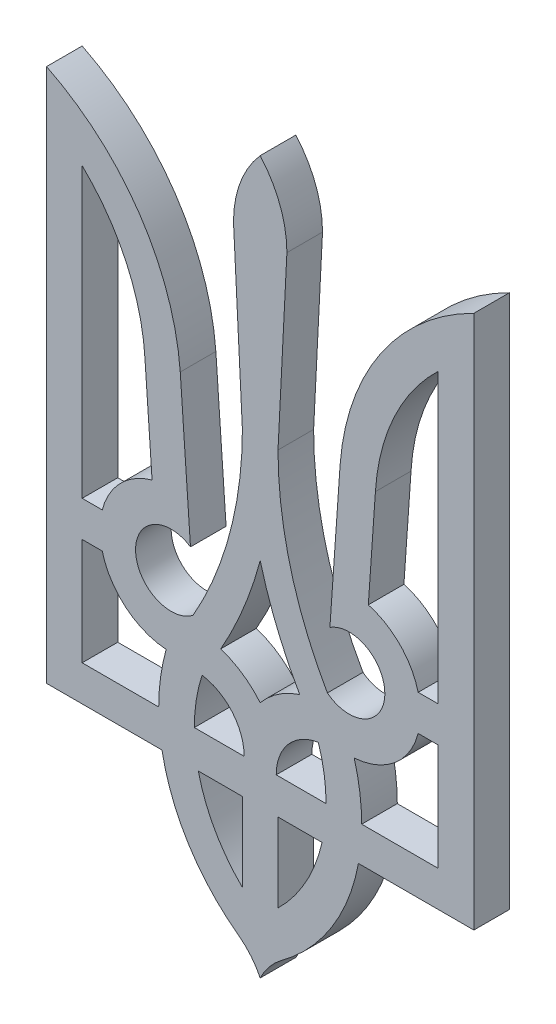
SolidWorks part; units mm, degrees
ref_plane "Спереди" through (0, 0, 0) normal (0, 0, 1) x (1, 0, 0)
ref_plane "Сверху" through (0, 0, 0) normal (0, 1, 0) x (1, 0, 0)
ref_plane "Справа" through (0, 0, 0) normal (1, 0, 0) x (0, 0, -1)
sketch "Эскиз1" plane through (0, 0, 0) normal (0, 0, 1) x (1, 0, 0)
  line L0 (0, 0) -> (-60, 0) construction
  line L1 (0, 0) -> (0, -45) construction
  line L2 (-27.5833, -45) -> (-60, -45)
  line L3 (-60, -45) -> (-60, 105)
  line L4 (-22.4495, 49.493) -> (-19.5761, 8.4012)
  line L5 (-22.38, 48.4989) -> (-20.3847, 19.9658) construction
  line L6 (0, 0) -> (15, 0) construction
  line L7 (0, -35) -> (26.5, -35) construction
  line L8 (0, -35) -> (-50, -35) construction
  line L9 (-28.5, -35) -> (-50, -35)
  line L10 (-50, -35) -> (-50, -5)
  line L11 (-50, 5) -> (-50, 85.9092)
  line L12 (-60, -45) -> (-90, -45) construction
  line L13 (-50, -35) -> (-50, 105) construction
  line L14 (-90, -45) -> (-90, 44.25) construction
  line L15 (0, 0) -> (0, 129.6666) construction
  line L16 (-60, 0) -> (-25, 0) construction
  line L17 (-44.3649, 5) -> (-50, 5)
  line L18 (-32.3556, 47.8014) -> (-30.3604, 19.2683)
  line L19 (-44.3649, -5) -> (-50, -5)
  line L20 (0, -45) -> (0, -95.3664) construction
  line L21 (-5, -67.1364) -> (-5, -45)
  line L22 (0, -45) -> (-60, -45) construction
  line L23 (-5, -45) -> (-17.3748, -45)
  line L24 (-18.5, -35) -> (-4.5, -35)
  line L25 (0, -45) -> (60, -45) construction
  line L26 (60, -45) -> (60, 93.5) construction
  line L27 (60, 93.5) -> (22.5, 93.5) construction
  line L28 (-90, 44.25) -> (-110, 44.25) construction
  line L29 (-7.5, 93.5) -> (0, 93.5) construction
  line L30 (-5, 44.25) -> (-7.5, 93.5)
  line L31 (0, -95.3664) -> (-18.004, -95.3664) construction
  line L32 (0, 113.3431) -> (0, -86.6569)
  arc A0 (-22.4495, 49.493) -> (-60, 105) centre (-90, 44.25) ccw
  arc A1 (-50, 85.9092) -> (-32.3556, 47.8014) centre (-90, 44.25) cw
  arc A2 (-44.3649, -5) -> (-26.4011, -19.9509) centre (-25, 0) ccw
  arc A3 (-19.5761, 8.4012) -> (-18.8639, -7.8961) centre (-25, 0) ccw
  arc A4 (-26.4011, -19.9509) -> (-28.5, -35) centre (26.5, -35) ccw
  arc A5 (-18.5, -35) -> (-16.3222, -21.1704) centre (26.5, -35) cw
  arc A6 (-27.5833, -45) -> (-5.9458, -79.4103) centre (26.5, -35) ccw
  arc A7 (-30.3604, 19.2683) -> (-44.3649, 5) centre (-25, 0) ccw
  arc A8 (-17.3748, -45) -> (-5, -67.1364) centre (26.5, -35) ccw
  arc A9 (-4.5, -35) -> (-16.3222, -21.1704) centre (-18.5, -35) ccw
  arc A10 (0, 113.3431) -> (-7.5, 93.5) centre (22.5, 93.5) ccw
  arc A11 (-18.8639, -7.8961) -> (-5, 44.25) centre (-110, 44.25) ccw
  arc A12 (0, -86.6569) -> (-5.9458, -79.4103) centre (-18.004, -95.3664) ccw
  arc A14 (0, -19.7111) -> (-11.0914, -12.1721) centre (-18.5, -35) ccw
  arc A16 (-11.0914, -12.1721) -> (0, 14.8157) centre (-110, 44.25) ccw
  point P3 (0, 5)
  point P7 (-87.4973, 5)
  point P8 (260.5938, -135.0208)
  point P9 (-87.4973, -5)
  point P26 (-19.6695, 9.7374)
  point P27 (-32.4251, 48.7954)
  point P28 (-29.6451, 9.0398)
  dimension "D9" = 135.5074
  dimension "D10" = 10
  dimension "D11" = 35
  dimension "D12" = 40
  dimension "D13" = 20
  dimension "D19" = 26.5
  dimension "D20" = 113.87
  dimension "D22" = 10
  dimension "D23" = 45
  dimension "D24" = 45
  dimension "D25" = 28
  dimension "D29" = 60
  dimension "D31" = 210
  dimension "D34" = 18.004
  dimension "D35" = 48
  dimension "D33" = 200
  dimension "D21" = 40
  dimension "D1" = 120
  dimension "D2" = 45
  dimension "D3" = 5
  dimension "D4" = 150
  dimension "D5" = 5
  dimension "D7" = 30
  dimension "D8" = 89.25
  dimension "D14" = 4
  dimension "D15" = 60.7207
  dimension "D17" = 21.5
  dimension "D18" = 15
  dimension "D26" = 60
  dimension "D27" = 138.5
  dimension "D28" = 37.5
  dimension "D30" = 20
  dimension "D32" = 7.5
  dimension "D36" = 200
  dimension "D6" = 10
  dimension "D16" = 10
extrude "Бобышка-Вытянуть1" add sketch "Эскиз1" along normal blind 10 contours A14 A16 L32 A10 L30 A11 A3 L4 A0 L3 L2 A6 A12 L18 A7 L17 L11 A1 A2 A4 L9 L10 L19 A8 L23 L21 A9 L24 A5
mirror "Зеркальное отражение1" about plane through (0, 0, 0) normal (1, 0, 0) of "Бобышка-Вытянуть1"
scale "Масштаб1" scale about centroid uniform scaling yes scale factor 0.5
